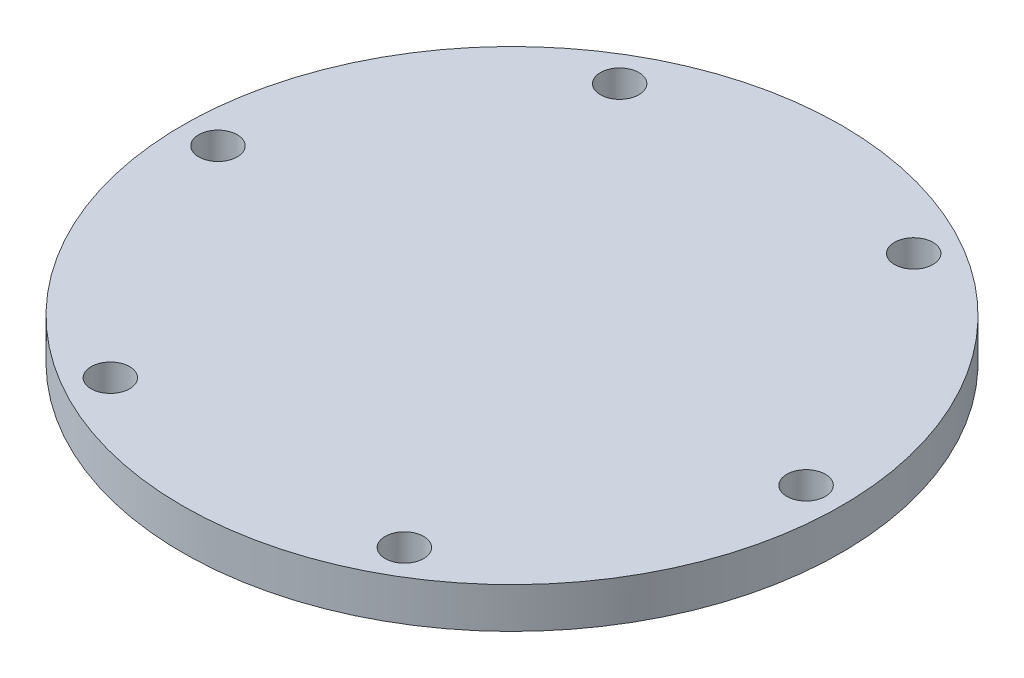
SolidWorks part; units mm, degrees
ref_plane "Front Plane" through (0, 0, 0) normal (0, 0, 1) x (1, 0, 0)
ref_plane "Top Plane" through (0, 0, 0) normal (0, 1, 0) x (1, 0, 0)
ref_plane "Right Plane" through (0, 0, 0) normal (1, 0, 0) x (0, 0, -1)
ref_axis "Center Axis" through (0, 18.669, 0) along (0, -1, 0)
sketch "Sketch1" plane through (0, 0, 0) normal (0, 1, 0) x (1, 0, 0)
  circle A0 centre (0, 0) radius 41.275
  dimension "D1" = 82.55
extrude "Body" add sketch "Sketch1" along normal blind 17.78
sketch "Sketch2" plane through (0, 0, 0) normal (0, -1, 0) x (1, 0, 0)
  circle A0 centre (0, 0) radius 32.385
  circle A1 centre (0, 0) radius 41.275
  dimension "D1" = 64.77
  dimension "D2" = 82.55
extrude "Bottom Initial" cut sketch "Sketch2" against normal blind 12.7
sketch "Sketch3" plane through (0, 0, 0) normal (0, -1, 0) x (1, 0, 0)
  circle A0 centre (0, 0) radius 13.97
  circle A1 centre (0, 0) radius 32.385
  dimension "D1" = 27.94
  dimension "D2" = 64.77
extrude "Bottom Stem" cut sketch "Sketch3" against normal blind 7.62
sketch "Sketch4" plane through (0, 0, 0) normal (0, 0, 1) x (1, 0, 0)
  line L0 (32.385, 8.89) -> (30.099, 8.89)
  line L1 (32.385, 7.62) -> (32.385, 12.7) construction
  line L2 (30.099, 8.89) -> (30.099, 11.43)
  line L3 (30.099, 11.43) -> (32.385, 11.43)
  line L4 (32.385, 11.43) -> (32.385, 8.89)
  line L5 (-32.385, 7.62) -> (32.385, 7.62) construction
  line L6 (-32.385, 12.7) -> (32.385, 12.7) construction
  dimension "D1" = 1.27
  dimension "D2" = 2.286
  dimension "D3" = 1.27
revolve "Top O ring" cut sketch "Sketch4" angle 360 about axis through (0, 18.669, 0) along (0, -1, 0)
sketch "Sketch5" plane through (0, 0, 0) normal (0, 0, 1) x (1, 0, 0)
  line L0 (13.97, 6.35) -> (11.684, 6.35)
  line L1 (13.97, 0) -> (13.97, 7.62) construction
  line L2 (11.684, 6.35) -> (11.684, 3.81)
  line L3 (11.684, 3.81) -> (13.97, 3.81)
  line L4 (13.97, 3.81) -> (13.97, 6.35)
  line L5 (-13.97, 7.62) -> (13.97, 7.62) construction
  dimension "D1" = 2.286
  dimension "D2" = 1.27
  dimension "D3" = 2.54
revolve "Bottom O ring" cut sketch "Sketch5" angle 360 about axis through (0, 18.669, 0) along (0, -1, 0)
chamfer "Chamfer1" distance 2.54 distance2 13.97 1 edges at (0, 0, -13.97)
sketch "Sketch9" plane through (0, 17.78, 0) normal (0, 1, 0) x (1, 0, 0)
  line L0 (0, 58.0915) -> (0, -55.9894) construction
  line L1 (-99.3126, 0) -> (81.4147, 0) construction
  circle A0 centre (-36.83, 0) radius 2.413
  dimension "D1" = 4.826
  dimension "D2" = 36.83
extrude "Cut-Extrude3" cut sketch "Sketch9" against normal up to next
pattern_circular "CirPattern1" count 6 over 360 about axis through (0, 0, 0) along (0, 1, 0) of "Cut-Extrude3"
